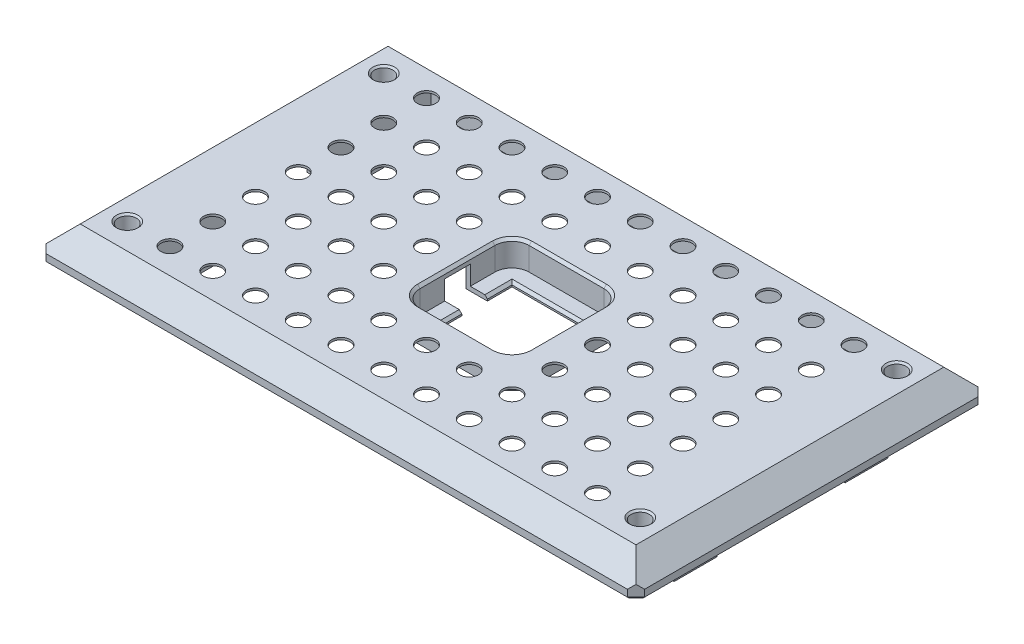
SolidWorks part; units mm, degrees
ref_plane "Front Plane" through (0, 0, 0) normal (0, 0, 1) x (1, 0, 0)
ref_plane "Top Plane" through (0, 0, 0) normal (0, 1, 0) x (1, 0, 0)
ref_plane "Right Plane" through (0, 0, 0) normal (1, 0, 0) x (0, 0, -1)
sketch "Sketch1" plane through (0, 0, 0) normal (0, 1, 0) x (1, 0, 0)
  line L1 (-70, -41) -> (70, -41)
  line L2 (-70, -41) -> (-70, 41)
  line L3 (-70, 41) -> (70, 41)
  line L4 (70, -41) -> (70, 41)
  line L5 (-70, -41) -> (70, 41) construction
  line L6 (-70, 41) -> (70, -41) construction
  point P0 (0, 0)
  dimension "D1" = 140
  dimension "D2" = 82
extrude "Boss-Extrude1" add sketch "Sketch1" along normal blind 2
sketch "Sketch2" plane through (0, 2, 0) normal (0, 1, 0) x (1, 0, 0)
  line L4 (70, -41) -> (70, 41)
  line L5 (70, 41) -> (-70, 41)
  line L6 (-70, 41) -> (-70, -41)
  line L7 (-70, -41) -> (70, -41)
  line L8 (70, -41) -> (70, 41)
  line L9 (70, 41) -> (-70, 41)
  line L10 (-70, 41) -> (-70, -41)
  line L11 (-70, -41) -> (70, -41)
  dimension "D1" = 0
ref_plane "Plane1" through (0, 7, 0) normal (0, 1, 0) x (1, 0, 0)
sketch "Sketch3" plane through (0, 7, 0) normal (0, 1, 0) x (1, 0, 0)
  line L0 (-70, 41) -> (-70, -41) construction
  line L1 (-65, -36) -> (65, -36)
  line L2 (-65, -36) -> (-65, 36)
  line L3 (-65, 36) -> (65, 36)
  line L4 (65, -36) -> (65, 36)
  line L5 (-65, -36) -> (65, 36) construction
  line L6 (-65, 36) -> (65, -36) construction
  line L7 (70, 41) -> (-70, 41) construction
  point P0 (0, 0)
  dimension "D1" = 5
  dimension "D2" = 5
loft "Loft1" add profiles "Sketch3", "Sketch2"
chamfer "Chamfer2" distance 2 angle 45 4 edges at (70, 1, 41) (70, 1, -41) (-70, 1, -41) (-70, 1, 41)
sketch "Sketch4" plane through (0, 0, 0) normal (0, -1, 0) x (1, 0, 0)
  line L0 (-70, -39) -> (-70, 39) construction
  line L1 (-62.9, 15) -> (-54.9, 15)
  line L2 (-62.9, 15) -> (-62.9, 25)
  line L3 (-62.9, 25) -> (-54.9, 25)
  line L4 (-54.9, 15) -> (-54.9, 25)
  line L5 (-62.9, 15) -> (-54.9, 25) construction
  line L6 (-62.9, 25) -> (-54.9, 15) construction
  line L7 (-70, 0) -> (70, 0) construction
  line L8 (70, 39) -> (70, -39) construction
  line L9 (0, 41) -> (0, -41) construction
  line L10 (-68, 41) -> (68, 41) construction
  line L11 (68, -41) -> (-68, -41) construction
  line L12 (-62.9, -25) -> (-54.9, -15) construction
  line L13 (-62.9, -15) -> (-54.9, -25) construction
  line L14 (-54.9, -15) -> (-54.9, -25)
  line L15 (-62.9, -25) -> (-54.9, -25)
  line L16 (-62.9, -15) -> (-62.9, -25)
  line L17 (-62.9, -15) -> (-54.9, -15)
  line L18 (62.9, -15) -> (54.9, -25) construction
  line L19 (62.9, -25) -> (54.9, -15) construction
  line L20 (62.9, 25) -> (54.9, 15) construction
  line L21 (62.9, 15) -> (54.9, 25) construction
  line L22 (62.9, -15) -> (54.9, -15)
  line L23 (62.9, -15) -> (62.9, -25)
  line L24 (62.9, -25) -> (54.9, -25)
  line L25 (54.9, -15) -> (54.9, -25)
  line L26 (54.9, 15) -> (54.9, 25)
  line L27 (62.9, 25) -> (54.9, 25)
  line L28 (62.9, 15) -> (62.9, 25)
  line L29 (62.9, 15) -> (54.9, 15)
  point P0 (-58.9, 20)
  point P21 (-58.9, -20)
  point P30 (58.9, -20)
  point P31 (58.9, 20)
  dimension "D1" = 10
  dimension "D2" = 7.1
  dimension "D3" = 8
  dimension "D4" = 40
extrude "Boss-Extrude2" add sketch "Sketch4" along normal blind 7
sketch "Sketch5" plane through (-62.9, 0, 0) normal (-1, 0, 0) x (0, 0, 1)
  line L0 (-15, 0) -> (-25, -7) construction
  line L1 (0, 0) -> (0, 50000) construction
  circle A0 centre (-20, -3.5) radius 2.05
  circle A1 centre (20, -3.5) radius 2.05
  dimension "D1" = 4.1
extrude "Cut-Extrude1" cut sketch "Sketch5" against normal through all
sketch "Sketch6" plane through (0, 0, 0) normal (0, -1, 0) x (1, 0, 0)
  line L0 (54.9, 25) -> (54.9, 15) construction
  line L1 (-53.9, -35) -> (53.9, -35)
  line L2 (-53.9, -35) -> (-53.9, 35)
  line L3 (-53.9, 35) -> (53.9, 35)
  line L4 (53.9, -35) -> (53.9, 35)
  line L5 (-53.9, -35) -> (53.9, 35) construction
  line L6 (-53.9, 35) -> (53.9, -35) construction
  line L8 (-65, 36) -> (65, 36) construction
  point P0 (0, 0)
  dimension "D1" = 1
  dimension "D2" = 1
extrude "Cut-Extrude2" cut sketch "Sketch6" against normal offset from surface (5.5 mm away) 1.5 up to face at (0, 7, 0)
sketch "Sketch7" plane through (0, 5.5, 0) normal (0, -1, 0) x (1, 0, 0)
  line L0 (0, 35) -> (0, -35) construction
  line L1 (-53.9, 35) -> (53.9, 35) construction
  line L2 (-53.9, -35) -> (53.9, -35) construction
  line L3 (-53.9, 0) -> (53.9, 0) construction
  line L4 (-53.9, -35) -> (-53.9, 35) construction
  line L5 (53.9, 35) -> (53.9, -35) construction
  circle A0 centre (0, 0) radius 2.15
  circle A1 centre (10, 0) radius 2.15
  circle A2 centre (20, 0) radius 2.15
  circle A3 centre (30, 0) radius 2.15
  circle A4 centre (40, 0) radius 2.15
  circle A5 centre (50, 0) radius 2.15
  circle A7 centre (10, 10) radius 2.15
  circle A8 centre (20, 10) radius 2.15
  circle A9 centre (30, 10) radius 2.15
  circle A10 centre (40, 10) radius 2.15
  circle A11 centre (50, 10) radius 2.15
  circle A13 centre (10, 20) radius 2.15
  circle A14 centre (20, 20) radius 2.15
  circle A15 centre (30, 20) radius 2.15
  circle A16 centre (40, 20) radius 2.15
  circle A17 centre (50, 20) radius 2.15
  circle A19 centre (10, 30) radius 2.15
  circle A20 centre (20, 30) radius 2.15
  circle A21 centre (30, 30) radius 2.15
  circle A22 centre (40, 30) radius 2.15
  circle A23 centre (50, 30) radius 2.15
  circle A25 centre (0, 10) radius 2.15
  circle A26 centre (0, 20) radius 2.15
  circle A27 centre (0, 30) radius 2.15
  circle A35 centre (-50, 30) radius 2.15
  circle A36 centre (-40, 30) radius 2.15
  circle A37 centre (-30, 30) radius 2.15
  circle A38 centre (-20, 30) radius 2.15
  circle A39 centre (-10, 30) radius 2.15
  circle A40 centre (-50, 20) radius 2.15
  circle A41 centre (-40, 20) radius 2.15
  circle A42 centre (-30, 20) radius 2.15
  circle A43 centre (-20, 20) radius 2.15
  circle A44 centre (-10, 20) radius 2.15
  circle A45 centre (-50, 10) radius 2.15
  circle A46 centre (-40, 10) radius 2.15
  circle A47 centre (-30, 10) radius 2.15
  circle A48 centre (-20, 10) radius 2.15
  circle A49 centre (-10, 10) radius 2.15
  circle A50 centre (-50, 0) radius 2.15
  circle A51 centre (-40, 0) radius 2.15
  circle A52 centre (-30, 0) radius 2.15
  circle A53 centre (-20, 0) radius 2.15
  circle A54 centre (-10, 0) radius 2.15
  circle A55 centre (-10, -10) radius 2.15
  circle A56 centre (-20, -10) radius 2.15
  circle A57 centre (-30, -10) radius 2.15
  circle A58 centre (-40, -10) radius 2.15
  circle A59 centre (-50, -10) radius 2.15
  circle A60 centre (-10, -20) radius 2.15
  circle A61 centre (-20, -20) radius 2.15
  circle A62 centre (-30, -20) radius 2.15
  circle A63 centre (-40, -20) radius 2.15
  circle A64 centre (-50, -20) radius 2.15
  circle A65 centre (-10, -30) radius 2.15
  circle A66 centre (-20, -30) radius 2.15
  circle A67 centre (-30, -30) radius 2.15
  circle A68 centre (-40, -30) radius 2.15
  circle A69 centre (-50, -30) radius 2.15
  circle A70 centre (0, -30) radius 2.15
  circle A71 centre (0, -20) radius 2.15
  circle A72 centre (0, -10) radius 2.15
  circle A73 centre (50, -30) radius 2.15
  circle A74 centre (40, -30) radius 2.15
  circle A75 centre (30, -30) radius 2.15
  circle A76 centre (20, -30) radius 2.15
  circle A77 centre (10, -30) radius 2.15
  circle A78 centre (50, -20) radius 2.15
  circle A79 centre (40, -20) radius 2.15
  circle A80 centre (30, -20) radius 2.15
  circle A81 centre (20, -20) radius 2.15
  circle A82 centre (10, -20) radius 2.15
  circle A83 centre (50, -10) radius 2.15
  circle A84 centre (40, -10) radius 2.15
  circle A85 centre (30, -10) radius 2.15
  circle A86 centre (20, -10) radius 2.15
  circle A87 centre (10, -10) radius 2.15
  dimension "D1" = 4.3
  dimension "D2" = 6
  dimension "D3" = 4
extrude "Cut-Extrude3" cut sketch "Sketch7" against normal through all
sketch "Sketch8" plane through (0, 5.5, 0) normal (0, -1, 0) x (1, 0, 0)
  line L0 (0, 35) -> (0, -35) construction
  line L1 (-53.9, 35) -> (53.9, 35) construction
  line L2 (53.9, -35) -> (-53.9, -35) construction
  line L3 (-53.9, 0) -> (53.9, 0) construction
  line L4 (-53.9, -35) -> (-53.9, 35) construction
  line L5 (53.9, -35) -> (53.9, 35) construction
  circle A0 centre (0, 0) radius 4.2
  circle A1 centre (10, 0) radius 4.2
  circle A2 centre (20, 0) radius 4.2
  circle A3 centre (30, 0) radius 4.2
  circle A4 centre (40, 0) radius 4.2
  circle A5 centre (50, 0) radius 4.2
  circle A6 centre (10, 10) radius 4.2
  circle A7 centre (20, 10) radius 4.2
  circle A8 centre (30, 10) radius 4.2
  circle A9 centre (40, 10) radius 4.2
  circle A10 centre (50, 10) radius 4.2
  circle A11 centre (10, 20) radius 4.2
  circle A12 centre (20, 20) radius 4.2
  circle A13 centre (30, 20) radius 4.2
  circle A14 centre (40, 20) radius 4.2
  circle A15 centre (50, 20) radius 4.2
  circle A16 centre (10, 30) radius 4.2
  circle A17 centre (20, 30) radius 4.2
  circle A18 centre (30, 30) radius 4.2
  circle A19 centre (40, 30) radius 4.2
  circle A20 centre (50, 30) radius 4.2
  circle A21 centre (0, 10) radius 4.2
  circle A22 centre (0, 20) radius 4.2
  circle A23 centre (0, 30) radius 4.2
  circle A24 centre (0, -30) radius 4.2
  circle A25 centre (0, -20) radius 4.2
  circle A26 centre (0, -10) radius 4.2
  circle A27 centre (50, -30) radius 4.2
  circle A28 centre (40, -30) radius 4.2
  circle A29 centre (30, -30) radius 4.2
  circle A30 centre (20, -30) radius 4.2
  circle A31 centre (10, -30) radius 4.2
  circle A32 centre (50, -20) radius 4.2
  circle A33 centre (40, -20) radius 4.2
  circle A34 centre (30, -20) radius 4.2
  circle A35 centre (20, -20) radius 4.2
  circle A36 centre (10, -20) radius 4.2
  circle A37 centre (50, -10) radius 4.2
  circle A38 centre (40, -10) radius 4.2
  circle A39 centre (30, -10) radius 4.2
  circle A40 centre (20, -10) radius 4.2
  circle A41 centre (10, -10) radius 4.2
  circle A42 centre (-10, -10) radius 4.2
  circle A43 centre (-20, -10) radius 4.2
  circle A44 centre (-30, -10) radius 4.2
  circle A45 centre (-40, -10) radius 4.2
  circle A46 centre (-50, -10) radius 4.2
  circle A47 centre (-10, -20) radius 4.2
  circle A48 centre (-20, -20) radius 4.2
  circle A49 centre (-30, -20) radius 4.2
  circle A50 centre (-40, -20) radius 4.2
  circle A51 centre (-50, -20) radius 4.2
  circle A52 centre (-10, -30) radius 4.2
  circle A53 centre (-20, -30) radius 4.2
  circle A54 centre (-30, -30) radius 4.2
  circle A55 centre (-40, -30) radius 4.2
  circle A56 centre (-50, -30) radius 4.2
  circle A57 centre (-50, 30) radius 4.2
  circle A58 centre (-40, 30) radius 4.2
  circle A59 centre (-30, 30) radius 4.2
  circle A60 centre (-20, 30) radius 4.2
  circle A61 centre (-10, 30) radius 4.2
  circle A62 centre (-50, 20) radius 4.2
  circle A63 centre (-40, 20) radius 4.2
  circle A64 centre (-30, 20) radius 4.2
  circle A65 centre (-20, 20) radius 4.2
  circle A66 centre (-10, 20) radius 4.2
  circle A67 centre (-50, 10) radius 4.2
  circle A68 centre (-40, 10) radius 4.2
  circle A69 centre (-30, 10) radius 4.2
  circle A70 centre (-20, 10) radius 4.2
  circle A71 centre (-10, 10) radius 4.2
  circle A72 centre (-50, 0) radius 4.2
  circle A73 centre (-40, 0) radius 4.2
  circle A74 centre (-30, 0) radius 4.2
  circle A75 centre (-20, 0) radius 4.2
  circle A76 centre (-10, 0) radius 4.2
  dimension "D1" = 8.4
  dimension "D2" = 6
  dimension "D3" = 4
extrude "Cut-Extrude4" cut sketch "Sketch8" against normal blind 1
sketch "Sketch9" plane through (0, 7, 0) normal (0, 1, 0) x (1, 0, 0)
  line L1 (53.9, -35) -> (34.6, -35)
  line L2 (53.9, -35) -> (53.9, -15.5)
  line L3 (53.9, -15.5) -> (34.6, -15.5)
  line L4 (34.6, -35) -> (34.6, -15.5)
  dimension "D1" = 19.3
  dimension "D2" = 19.5
sketch "Sketch13" plane through (0, 5.5, 0) normal (0, -1, 0) x (1, 0, 0)
  circle A0 centre (50, 20) radius 4.2 construction
  circle A1 centre (40, 20) radius 4.2 construction
  circle A2 centre (40, 30) radius 4.2 construction
  circle A3 centre (50, 30) radius 4.2 construction
  circle A4 centre (50, 20) radius 4.2
  circle A5 centre (40, 20) radius 4.2
  circle A6 centre (40, 30) radius 4.2
  circle A7 centre (50, 30) radius 4.2
extrude "Boss-Extrude4" [suppressed] add sketch "Sketch13" against normal up to surface (1.5 mm away)
sketch "Sketch10" plane through (0, 5.5, 0) normal (0, -1, 0) x (1, 0, 0)
  line L1 (53.9, 35) -> (43.9, 35) construction
  line L2 (53.9, 35) -> (53.9, 25) construction
  line L3 (53.9, 25) -> (43.9, 25) construction
  line L4 (43.9, 35) -> (43.9, 25) construction
  circle A0 centre (43.9, 25) radius 3.3
  dimension "D1" = 6.6
  dimension "D2" = 10
extrude "Cut-Extrude5" [suppressed] cut sketch "Sketch10" against normal through all
sketch "Sketch11" plane through (0, 0, 0) normal (0, -1, 0) x (1, 0, 0)
  line L0 (53.9, 35) -> (53.9, 31.5588) construction
  line L1 (53.9, 10) -> (63.9, 10)
  line L2 (53.9, 10) -> (53.9, -10)
  line L3 (53.9, -10) -> (63.9, -10)
  line L4 (63.9, 10) -> (63.9, -10)
  line L5 (-53.9, 35) -> (-53.9, -35) construction
  line L6 (-53.9, 10) -> (-63.9, 10)
  line L7 (-53.9, 10) -> (-53.9, -10)
  line L8 (-53.9, -10) -> (-63.9, -10)
  line L9 (-63.9, 10) -> (-63.9, -10)
  line L10 (-70, -39) -> (-70, 39) construction
  point P12 (-63.9, 0)
  point P15 (-70, 0)
  point P16 (63.9, 0)
  dimension "D1" = 10
  dimension "D2" = 20
extrude "Cut-Extrude6" cut sketch "Sketch11" against normal up to surface (5.5 mm away) up to face at (10, 5.5, -5.8)
sketch "Sketch12" plane through (0, 0, 0) normal (0, -1, 0) x (1, 0, 0)
  line L0 (0, 0) -> (-60, 0) construction
  line L1 (-60, -30) -> (-60, 30) construction
  line L2 (-70, -39) -> (-70, 39) construction
  line L3 (0, 41) -> (0, -41) construction
  line L4 (-68, 41) -> (68, 41) construction
  line L5 (68, -41) -> (-68, -41) construction
  line L6 (60, -30) -> (60, 30) construction
  circle A0 centre (-60, 30) radius 2.15
  circle A1 centre (-60, -30) radius 2.15
  circle A2 centre (60, -30) radius 2.15
  circle A3 centre (60, 30) radius 2.15
  point P6 (-60, 0)
  point P20 (60, 0)
  dimension "D1" = 4.3
  dimension "D2" = 60
  dimension "D3" = 10
extrude "Cut-Extrude7" cut sketch "Sketch12" against normal through all
chamfer "Chamfer3" distance 0.4 angle 45 8 edges at (-69, 0, -40) (-70, 0, 0) (-69, 0, 40) (0, 0, 41) (69, 0, 40) (70, 0, 0) (69, 0, -40) (0, 0, -41)
chamfer "Chamfer4" distance 0.4 angle 45 4 edges at (60, 7, 27.85) (60, 7, -32.15) (-60, 7, 27.85) (-60, 7, -32.15)
chamfer "Chamfer5" distance 0.4 angle 45 4 edges at (-62.9, -3.5, 17.95) (-62.9, -3.5, -17.95) (62.9, -3.5, 22.05) (62.9, -3.5, -17.95)
sketch "Sketch14" plane through (0, 5.5, 0) normal (0, -1, 0) x (1, 0, 0)
  line L1 (-15, -15) -> (15, -15)
  line L2 (-15, -15) -> (-15, 15)
  line L3 (-15, 15) -> (15, 15)
  line L4 (15, -15) -> (15, 15)
  line L5 (-15, -15) -> (15, 15) construction
  line L6 (-15, 15) -> (15, -15) construction
  point P0 (0, 0)
  dimension "D1" = 30
extrude "Boss-Extrude5" add sketch "Sketch14" against normal up to surface (1.5 mm away) up to face at (60, 7, 27.45)
sketch "Sketch15" plane through (0, 7, 0) normal (0, 1, 0) x (1, 0, 0)
  line L1 (-8.75, -12.75) -> (8.75, -12.75)
  line L2 (-12.75, -8.75) -> (-12.75, 8.75)
  line L3 (-8.75, 12.75) -> (8.75, 12.75)
  line L4 (12.75, -8.75) -> (12.75, 8.75)
  line L5 (-12.75, -12.75) -> (12.75, 12.75) construction
  line L6 (-12.75, 12.75) -> (12.75, -12.75) construction
  arc A0 (8.75, 12.75) -> (12.75, 8.75) centre (8.75, 8.75) cw
  arc A1 (12.75, -8.75) -> (8.75, -12.75) centre (8.75, -8.75) cw
  arc A2 (-8.75, -12.75) -> (-12.75, -8.75) centre (-8.75, -8.75) cw
  arc A3 (-12.75, 8.75) -> (-8.75, 12.75) centre (-8.75, 8.75) cw
  point P0 (0, 0)
  dimension "D2" = 4
  dimension "D1" = 25.5
extrude "Cut-Extrude8" cut sketch "Sketch15" against normal through all and the other way through all
sketch "Sketch16" plane through (0, 5.5, 0) normal (0, -1, 0) x (1, 0, 0)
  line L0 (12.75, -8.75) -> (12.75, 8.75) construction
  line L1 (-8.75, -12.75) -> (8.75, -12.75) construction
  line L2 (-12.75, 8.75) -> (-12.75, -8.75) construction
  line L3 (8.75, 12.75) -> (-8.75, 12.75) construction
  line L4 (12.75, -8.75) -> (12.75, 8.75)
  line L5 (-8.75, -12.75) -> (8.75, -12.75)
  line L6 (-12.75, 8.75) -> (-12.75, -8.75)
  line L7 (8.75, 12.75) -> (-8.75, 12.75)
  line L8 (-13.75, 8.75) -> (-13.75, -8.75)
  line L9 (-8.75, -13.75) -> (8.75, -13.75)
  line L10 (13.75, -8.75) -> (13.75, 8.75)
  line L11 (8.75, 13.75) -> (-8.75, 13.75)
  arc A0 (12.75, 8.75) -> (8.75, 12.75) centre (8.75, 8.75) ccw construction
  arc A1 (8.75, -12.75) -> (12.75, -8.75) centre (8.75, -8.75) ccw construction
  arc A2 (-12.75, -8.75) -> (-8.75, -12.75) centre (-8.75, -8.75) ccw construction
  arc A3 (-8.75, 12.75) -> (-12.75, 8.75) centre (-8.75, 8.75) ccw construction
  arc A4 (12.75, 8.75) -> (8.75, 12.75) centre (8.75, 8.75) ccw
  arc A5 (8.75, -12.75) -> (12.75, -8.75) centre (8.75, -8.75) ccw
  arc A6 (-12.75, -8.75) -> (-8.75, -12.75) centre (-8.75, -8.75) ccw
  arc A7 (-8.75, 12.75) -> (-12.75, 8.75) centre (-8.75, 8.75) ccw
  arc A8 (-8.75, 13.75) -> (-13.75, 8.75) centre (-8.75, 8.75) ccw
  arc A9 (-13.75, -8.75) -> (-8.75, -13.75) centre (-8.75, -8.75) ccw
  arc A10 (8.75, -13.75) -> (13.75, -8.75) centre (8.75, -8.75) ccw
  arc A11 (13.75, 8.75) -> (8.75, 13.75) centre (8.75, 8.75) ccw
  dimension "D1" = 1
extrude "Boss-Extrude6" add sketch "Sketch16" along normal blind 4.5
sketch "Sketch17" plane through (0, 1, 0) normal (0, -1, 0) x (1, 0, 0)
  line L1 (-8.75, -8.75) -> (8.75, -8.75)
  line L2 (-8.75, -8.75) -> (-8.75, 8.75)
  line L3 (-8.75, 8.75) -> (8.75, 8.75)
  line L4 (-13.75, 8.75) -> (-13.75, -8.75)
  line L5 (-8.75, -13.75) -> (8.75, -13.75)
  line L6 (13.75, -8.75) -> (13.75, 8.75)
  line L7 (8.75, 13.75) -> (-8.75, 13.75)
  line L8 (-13.75, 8.75) -> (-13.75, -8.75)
  line L9 (-8.75, -13.75) -> (8.75, -13.75)
  line L10 (13.75, -8.75) -> (13.75, 8.75)
  line L11 (8.75, 13.75) -> (-8.75, 13.75)
  line L12 (8.75, -8.75) -> (8.75, 8.75)
  line L13 (-8.75, -8.75) -> (8.75, 8.75) construction
  line L14 (-8.75, 8.75) -> (8.75, -8.75) construction
  arc A4 (-8.75, 13.75) -> (-13.75, 8.75) centre (-8.75, 8.75) ccw
  arc A5 (-13.75, -8.75) -> (-8.75, -13.75) centre (-8.75, -8.75) ccw
  arc A6 (8.75, -13.75) -> (13.75, -8.75) centre (8.75, -8.75) ccw
  arc A7 (13.75, 8.75) -> (8.75, 13.75) centre (8.75, 8.75) ccw
  arc A8 (-8.75, 13.75) -> (-13.75, 8.75) centre (-8.75, 8.75) ccw
  arc A9 (-13.75, -8.75) -> (-8.75, -13.75) centre (-8.75, -8.75) ccw
  arc A10 (8.75, -13.75) -> (13.75, -8.75) centre (8.75, -8.75) ccw
  arc A11 (13.75, 8.75) -> (8.75, 13.75) centre (8.75, 8.75) ccw
  point P0 (0, 0)
  dimension "D1" = 0
extrude "Boss-Extrude7" add sketch "Sketch17" along normal blind 1
sketch "Sketch18" plane through (0, 0, 0) normal (0, -1, 0) x (1, 0, 0)
  line L0 (-13.75, 8.75) -> (-13.75, -8.75) construction
  line L1 (-13.75, 3) -> (-8.75, 3)
  line L2 (-13.75, 3) -> (-13.75, -3)
  line L3 (-13.75, -3) -> (-8.75, -3)
  line L4 (-8.75, 3) -> (-8.75, -3)
  line L5 (-8.75, 8.75) -> (-8.75, -8.75) construction
  point P8 (-8.75, 0)
  dimension "D1" = 6
extrude "Cut-Extrude9" cut sketch "Sketch18" against normal up to surface (5.5 mm away)
chamfer "Chamfer6" distance 0.6 angle 45 8 edges at (0, 7, -12.75) (11.5784, 7, -11.5784) (-11.5784, 7, -11.5784) (12.75, 7, 0) (-12.75, 7, 0) (11.5784, 7, 11.5784) (-11.5784, 7, 11.5784) (0, 7, 12.75)
chamfer "Chamfer7" distance 0.6 angle 45 5 edges at (-8.75, 1, -5.875) (0, 1, -8.75) (8.75, 1, 0) (-8.75, 1, 5.875) (0, 1, 8.75)
